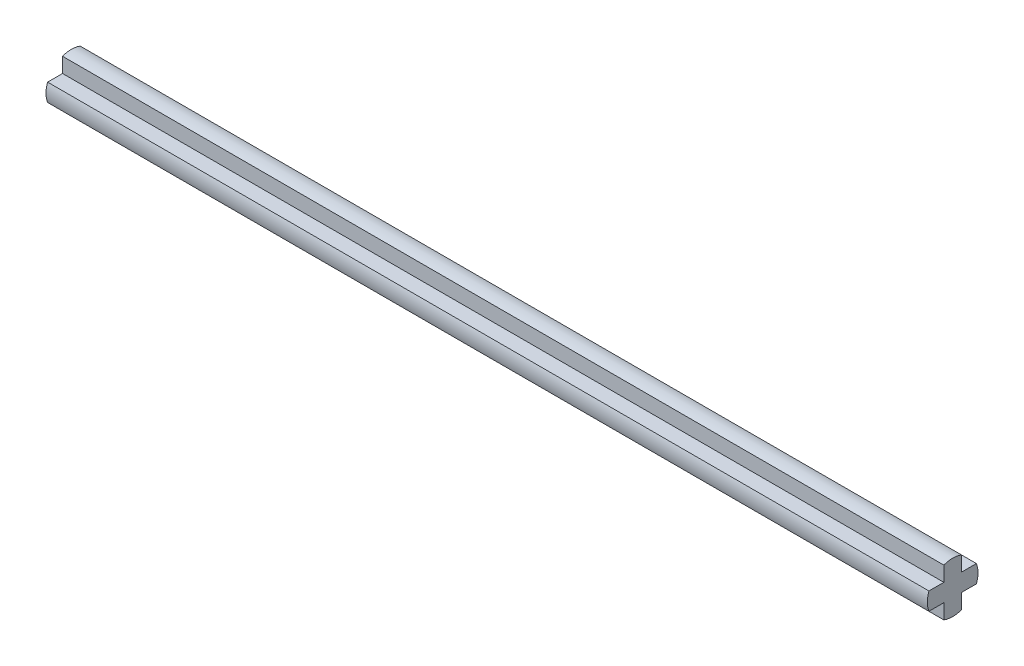
SolidWorks part; units mm, degrees
ref_plane "Front Plane" through (0, 0, 0) normal (0, 0, 1) x (1, 0, 0)
ref_plane "Top Plane" through (0, 0, 0) normal (0, 1, 0) x (1, 0, 0)
ref_plane "Right Plane" through (0, 0, 0) normal (1, 0, 0) x (0, 0, -1)
sketch "Sketch1" plane through (0, 0, 0) normal (1, 0, 0) x (0, 0, -1)
  line L0 (-2.1564, 0.8) -> (-0.8, 0.8)
  line L1 (2.1564, -0.8) -> (-2.1564, -0.8) construction
  line L2 (2.1564, -0.8) -> (2.1564, 0.8) construction
  line L3 (2.1564, 0.8) -> (-2.1564, 0.8) construction
  line L4 (-2.1564, -0.8) -> (-2.1564, 0.8) construction
  line L5 (2.1564, -0.8) -> (-2.1564, 0.8) construction
  line L6 (2.1564, 0.8) -> (-2.1564, -0.8) construction
  line L7 (-0.8, -2.1564) -> (0.8, -2.1564) construction
  line L8 (-0.8, -2.1564) -> (-0.8, 2.1564) construction
  line L9 (-0.8, 2.1564) -> (0.8, 2.1564) construction
  line L10 (0.8, -2.1564) -> (0.8, 2.1564) construction
  line L11 (-0.8, -2.1564) -> (0.8, 2.1564) construction
  line L12 (-0.8, 2.1564) -> (0.8, -2.1564) construction
  line L13 (-0.8, 0.8) -> (-0.8, 2.1564)
  line L14 (0.8, 2.1564) -> (0.8, 0.8)
  line L15 (0.8, 0.8) -> (2.1564, 0.8)
  line L16 (2.1564, -0.8) -> (0.8, -0.8)
  line L17 (0.8, -0.8) -> (0.8, -2.1564)
  line L18 (-0.8, -2.1564) -> (-0.8, -0.8)
  line L19 (-0.8, -0.8) -> (-2.1564, -0.8)
  circle A0 centre (0, 0) radius 2.3 construction
  spline S0 degree 2 poles (-2.1564, -0.8) (-2.4436, 0) (-2.1564, 0.8) knots 0 0 0 1 1 1
  spline S1 degree 2 poles (-0.8, 2.1564) (0, 2.4436) (0.8, 2.1564) knots 0 0 0 1 1 1
  spline S2 degree 2 poles (2.1564, 0.8) (2.4436, 0) (2.1564, -0.8) knots 0 0 0 1 1 1
  spline S3 degree 2 poles (0.8, -2.1564) (0, -2.4436) (-0.8, -2.1564) knots 0 0 0 1 1 1
  point P18 (0, 0)
  dimension "D1" = 4.6
  dimension "D2" = 1.6
  dimension "D3" = 1.6
extrude "Boss-Extrude1" add sketch "Sketch1" along normal blind 80
